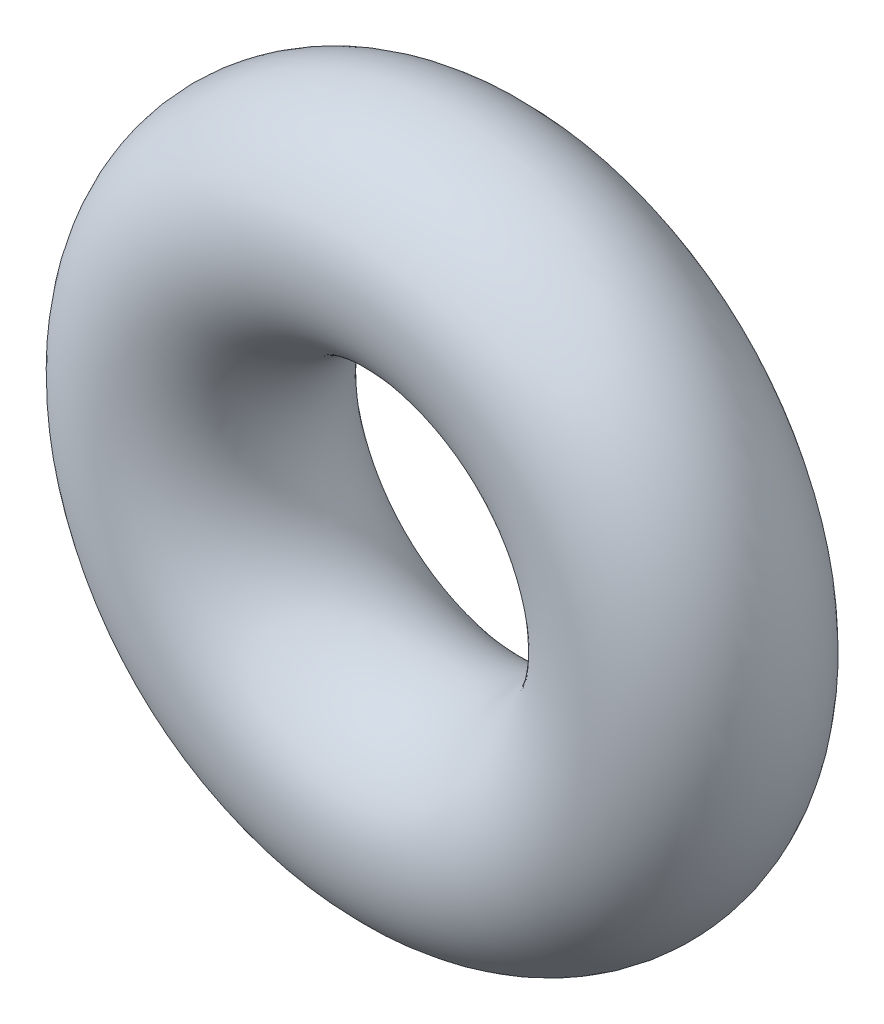
SolidWorks part; units mm, degrees
ref_plane "前视基准面" through (0, 0, 0) normal (0, 0, 1) x (1, 0, 0)
ref_plane "上视基准面" through (0, 0, 0) normal (0, 1, 0) x (1, 0, 0)
ref_plane "右视基准面" through (0, 0, 0) normal (1, 0, 0) x (0, 0, -1)
sketch "草图1" plane through (0, 0, 0) normal (0, 0, 1) x (1, 0, 0)
  circle A0 centre (0, 0) radius 148.75
  dimension "D1" = 297.5
sketch "草图2" plane through (0, 0, 0) normal (0, 1, 0) x (1, 0, 0)
  line L0 (-148.75, 0) -> (148.75, 0) construction
  circle A0 centre (-148.75, 0) radius 67.5
  dimension "D1" = 135
sweep "扫描1" add profiles "草图2" path "草图1"
sketch "草图3" plane through (0, 0, 0) normal (0, 0, 1) x (1, 0, 0)
  line L0 (-216.25, 0) -> (216.25, 0) construction
  line L1 (-81.25, 0) -> (-216.25, 0) construction
  line L2 (0, 0) -> (0, 100.1348) construction
  circle A0 centre (0, 0) radius 216.25 construction
sketch "草图4" plane through (0, 0, 0) normal (0, 1, 0) x (1, 0, 0)
  line L1 (-216.25, 0) -> (216.25, 0) construction
  circle A0 centre (148.75, 0) radius 67.5 construction
  point P2 (216.25, 0)
  point P5 (0, 0)
  point P6 (216.25, 0)
  point P9 (216.25, 0)
  dimension "D1" = 135
  dimension "D2" = 67.5
